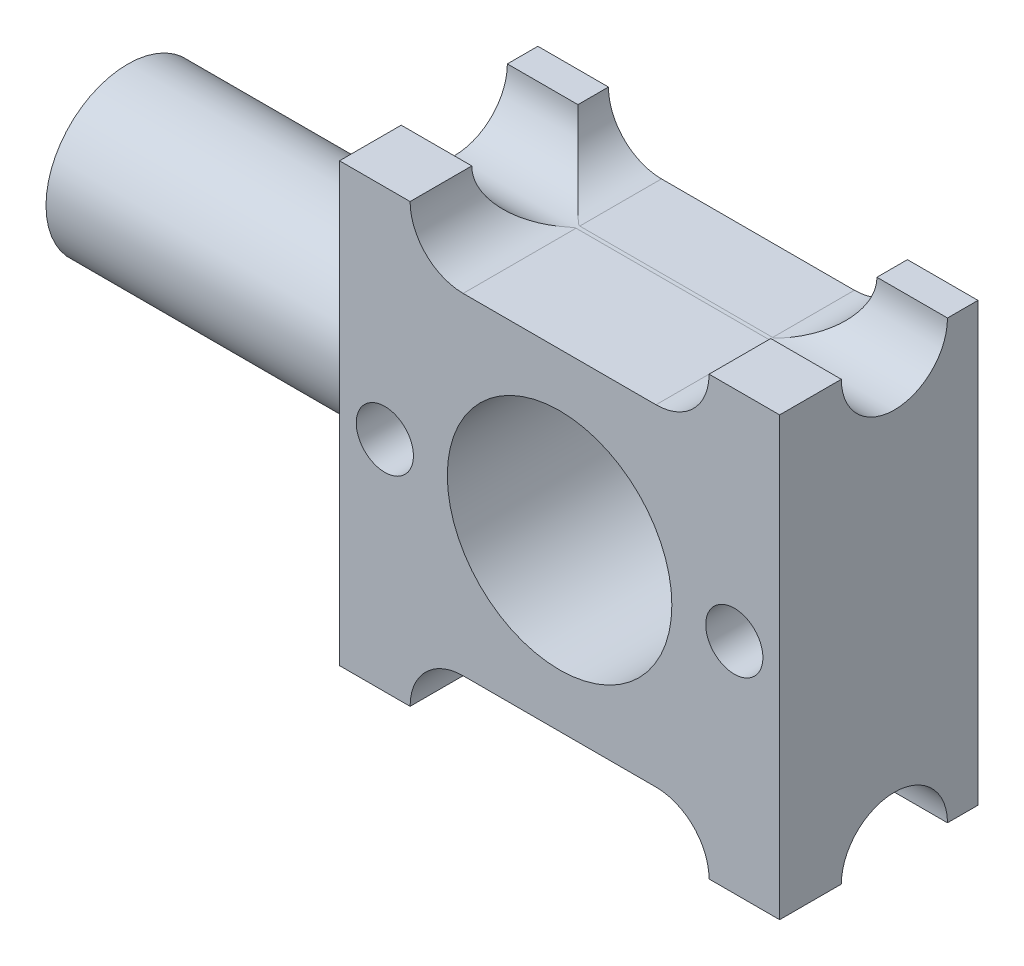
SolidWorks part; units mm, degrees
ref_plane "Front Plane" through (0, 0, 0) normal (0, 0, 1) x (1, 0, 0)
ref_plane "Top Plane" through (0, 0, 0) normal (0, 1, 0) x (1, 0, 0)
ref_plane "Right Plane" through (0, 0, 0) normal (1, 0, 0) x (0, 0, -1)
sketch "Sketch1" plane through (0, 0, 0) normal (0, 0, 1) x (1, 0, 0)
  line L1 (-6.8453, 6.8) -> (6.8453, 6.8)
  line L2 (-6.8453, 6.8) -> (-6.8453, -6.8)
  line L3 (-6.8453, -6.8) -> (6.8453, -6.8)
  line L4 (6.8453, 6.8) -> (6.8453, -6.8)
  line L5 (-6.8453, 6.8) -> (6.8453, -6.8) construction
  line L6 (-6.8453, -6.8) -> (6.8453, 6.8) construction
  point P0 (0, 0)
  dimension "D1" = 13.6906
  dimension "D2" = 13.6
extrude "Boss-Extrude1" add sketch "Sketch1" along normal blind 6.17
sketch "Sketch2" plane through (6.8453, 0, 0) normal (1, 0, 0) x (0, 0, -1)
  line L0 (-6.17, 6.8) -> (0, 6.8) construction
  line L1 (0, -6.8) -> (0, 6.8) construction
  line L2 (-6.17, 0) -> (0, 0) construction
  line L3 (-6.17, -6.8) -> (-6.17, 6.8) construction
  circle A0 centre (-2.6, 6.8) radius 1.651
  circle A1 centre (-2.6, -6.8) radius 1.651
  dimension "D2" = 3.302
  dimension "D1" = 2.6
extrude "Cut-Extrude1" cut sketch "Sketch2" against normal through all
sketch "Sketch3" plane through (0, 0, 6.17) normal (0, 0, 1) x (1, 0, 0)
  line L0 (6.8453, 6.8) -> (-6.8453, 6.8) construction
  line L1 (-3, 6.8) -> (3, 6.8)
  line L2 (-3, 6.8) -> (-3, 5.15)
  line L3 (-3, 5.15) -> (3, 5.15)
  line L4 (3, 6.8) -> (3, 5.15)
  line L5 (0, 5.15) -> (0, 7.1831) construction
  line L6 (-6.8453, 0) -> (0, 5.15) construction
  line L7 (-6.8453, 6.8) -> (-6.8453, -6.8) construction
  line L8 (0, 5.15) -> (6.8453, 0) construction
  line L9 (6.8453, -6.8) -> (6.8453, 6.8) construction
  line L10 (-6.8453, 0) -> (6.8453, 0) construction
  line L11 (0, -5.15) -> (6.8453, 0) construction
  line L12 (-6.8453, 0) -> (0, -5.15) construction
  line L13 (0, -5.15) -> (0, -7.1831) construction
  line L14 (3, -6.8) -> (3, -5.15)
  line L15 (-3, -5.15) -> (3, -5.15)
  line L16 (-3, -6.8) -> (-3, -5.15)
  line L17 (-3, -6.8) -> (3, -6.8)
  line L18 (-4.65, 6.8) -> (4.65, 6.8)
  line L19 (-3, -6.8) -> (3, -6.8)
  arc A0 (3, 5.15) -> (4.65, 6.8) centre (3, 6.8) ccw
  arc A1 (-3, 5.15) -> (-4.65, 6.8) centre (-3, 6.8) cw
  arc A2 (-3, -5.15) -> (-4.65, -6.8) centre (-3, -6.8) ccw
  arc A3 (3, -5.15) -> (4.65, -6.8) centre (3, -6.8) cw
  line M9 (6.8453, 6.8) -> (-6.8453, 6.8)
  line M11 (-6.8453, -6.8) -> (6.8453, -6.8)
  dimension "D2" = 1.65
  dimension "D1" = 1.65
  dimension "D3" = 6
extrude "Cut-Extrude2" cut sketch "Sketch3" against normal through all contours A1 L2 M9 | L4 L2 L3 M9 | L4 A0 M9 | A3 L14 M11 | L16 L14 L15 M11 | L16 A2 M11
sketch "Sketch4" plane through (0, 0, 6.17) normal (0, 0, 1) x (1, 0, 0)
  circle A0 centre (0, 0) radius 3.4925
  dimension "D1" = 6.985
extrude "Cut-Extrude3" cut sketch "Sketch4" against normal through all
sketch "Sketch5" plane through (-6.8453, 0, 0) normal (-1, 0, 0) x (0, 0, 1)
  line L0 (2.6, 5.149) -> (2.6, -5.149) construction
  circle A0 centre (2.6, 0) radius 2.54
  arc A2 (0.949, 6.8) -> (4.251, 6.8) centre (2.6, 6.8) ccw construction
  arc A3 (4.251, -6.8) -> (0.949, -6.8) centre (2.6, -6.8) ccw construction
  dimension "D1" = 5.08
extrude "Boss-Extrude2" add sketch "Sketch5" along normal blind 10.16
sketch "Sketch6" plane through (0, 0, 6.17) normal (0, 0, 1) x (1, 0, 0)
  line L0 (0, 5.15) -> (0, -5.15) construction
  line L1 (-3, 5.15) -> (3, 5.15) construction
  line L2 (-3, -5.15) -> (3, -5.15) construction
  circle A0 centre (-5.4356, 0) radius 0.889
  circle A1 centre (5.4356, 0) radius 0.889
  dimension "D1" = 1.778
  dimension "D2" = 10.8712
extrude "Cut-Extrude4" cut sketch "Sketch6" against normal through all
